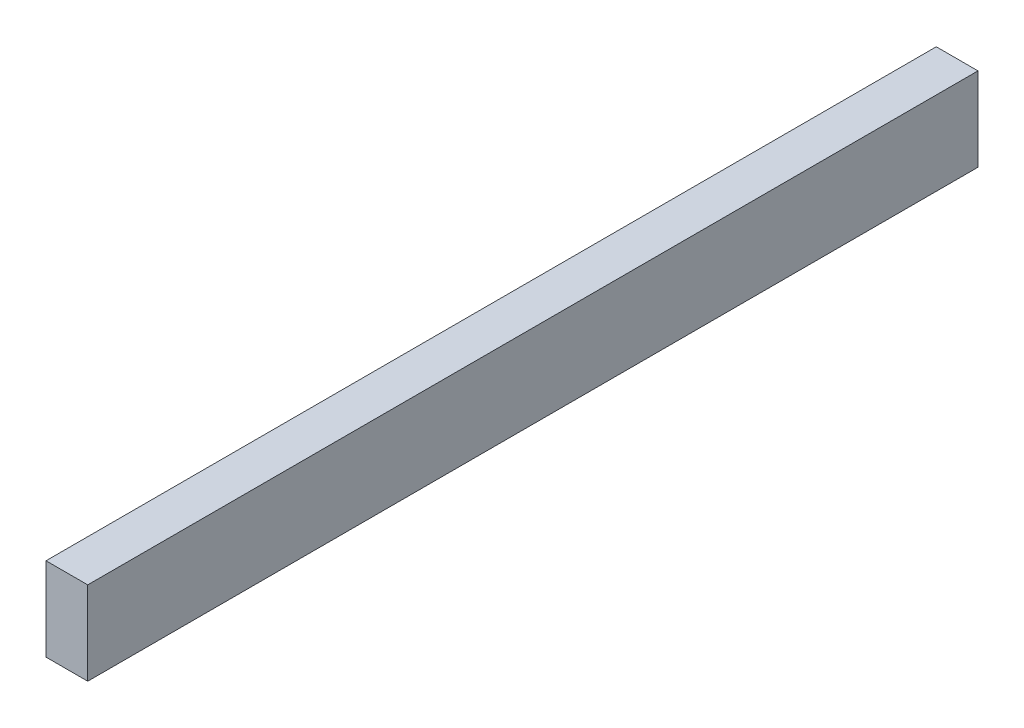
SolidWorks part; units mm, degrees
ref_plane "Plano frontal" through (0, 0, 0) normal (0, 0, 1) x (1, 0, 0)
ref_plane "Plano superior" through (0, 0, 0) normal (0, 1, 0) x (1, 0, 0)
ref_plane "Plano direito" through (0, 0, 0) normal (1, 0, 0) x (0, 0, -1)
sketch "Esboço1" plane through (0, 0, 0) normal (1, 0, 0) x (0, 0, -1)
  line L1 (-160, 15) -> (160, 15)
  line L2 (-160, 15) -> (-160, -15)
  line L3 (-160, -15) -> (160, -15)
  line L4 (160, 15) -> (160, -15)
  line L5 (-160, 15) -> (160, -15) construction
  line L6 (-160, -15) -> (160, 15) construction
  point P0 (0, 0)
  dimension "D1" = 320
  dimension "D2" = 30
extrude "Ressalto-extrusão1" add sketch "Esboço1" along normal blind 15
